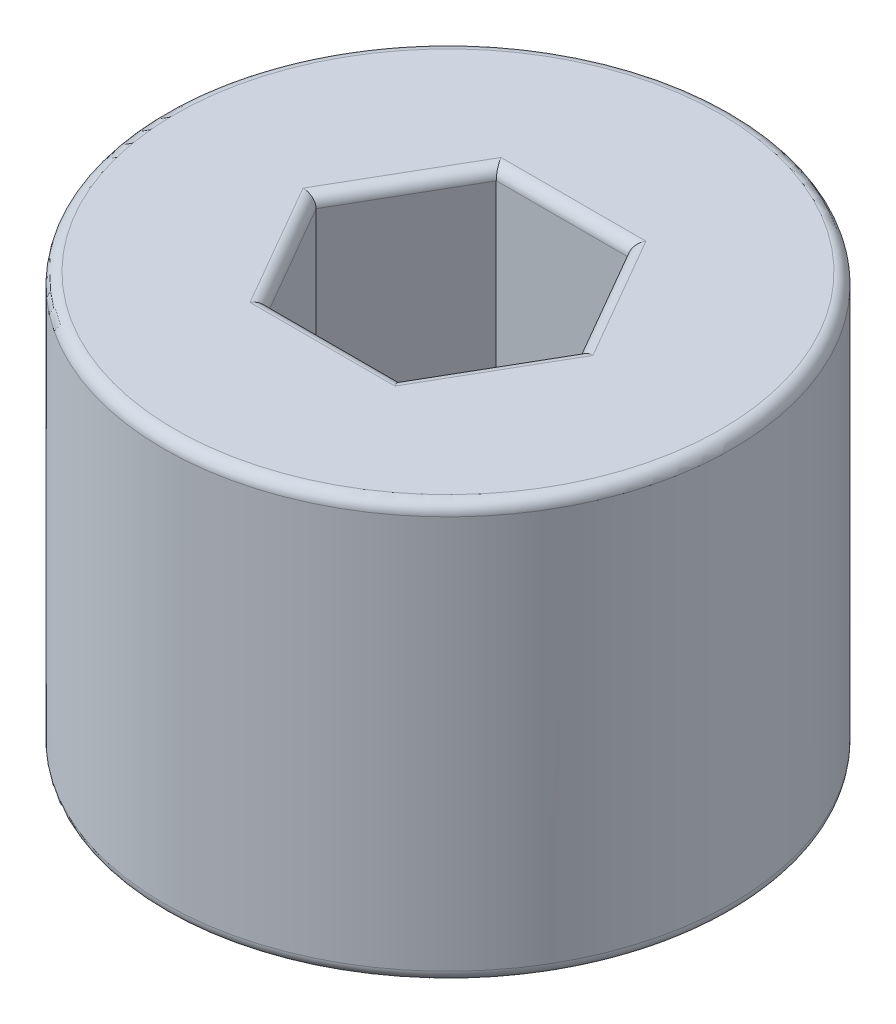
SolidWorks part; units mm, degrees
material "ABS"
ref_plane "Front Plane" through (0, 0, 0) normal (0, 0, 1) x (1, 0, 0)
ref_plane "Top Plane" through (0, 0, 0) normal (0, 1, 0) x (1, 0, 0)
ref_plane "Right Plane" through (0, 0, 0) normal (1, 0, 0) x (0, 0, -1)
sketch "Sketch3" plane through (0, 0, 0) normal (1, 0, 0) x (0, 0, -1)
  line L0 (0, 17.1606) -> (0, -12.041) construction
  line L1 (6.4135, 0) -> (6.4135, -25.9842)
  line L2 (6.4135, -25.9842) -> (10.16, -25.9842)
  line L3 (10.16, -25.9842) -> (10.16, -23.368)
  line L4 (10.16, -23.368) -> (15.9639, -23.368)
  line L5 (15.9639, -23.368) -> (15.9639, 0)
  line L6 (15.9639, 0) -> (6.4135, 0)
  dimension "D1" = 25.9842
  dimension "D2" = 12.827
  dimension "D3" = 31.9278
  dimension "D4" = 23.368
  dimension "D5" = 20.32
revolve "Revolve1" add sketch "Sketch3" angle 360 about L0
sketch "Sketch2" plane through (0, 0, 0) normal (0, 1, 0) x (1, 0, 0)
  line L1 (7.4057, 0) -> (3.7028, 6.4135)
  line L2 (3.7028, 6.4135) -> (-3.7028, 6.4135)
  line L3 (-3.7028, 6.4135) -> (-7.4057, 0)
  line L4 (-7.4057, 0) -> (-3.7028, -6.4135)
  line L5 (-3.7028, -6.4135) -> (3.7028, -6.4135)
  line L6 (3.7028, -6.4135) -> (7.4057, 0)
  circle A0 centre (0, 0) radius 6.4135 construction
  circle A1 centre (0, 0) radius 6.4135 construction
extrude "Cut-Extrude1" cut sketch "Sketch2" against normal through all
fillet "Fillet1" radius 0.635 15 edges at (0, -23.368, 15.9639) (0, -25.9842, -6.4135) (5.5543, -25.9842, -3.2068) (5.5543, -25.9842, 3.2067) (0, -25.9842, 6.4135) (-5.5543, -25.9842, 3.2068) (-5.5543, -25.9842, -3.2067) (0, -25.9842, 10.16) (0, 0, 15.9639) (0, 0, -6.4135) (-5.5543, 0, -3.2067) (-5.5543, 0, 3.2068) (0, 0, 6.4135) (5.5543, 0, 3.2067) (5.5543, 0, -3.2068)
fillet "Fillet2" radius 2.032 1 edges at (0, -23.368, 10.16)
